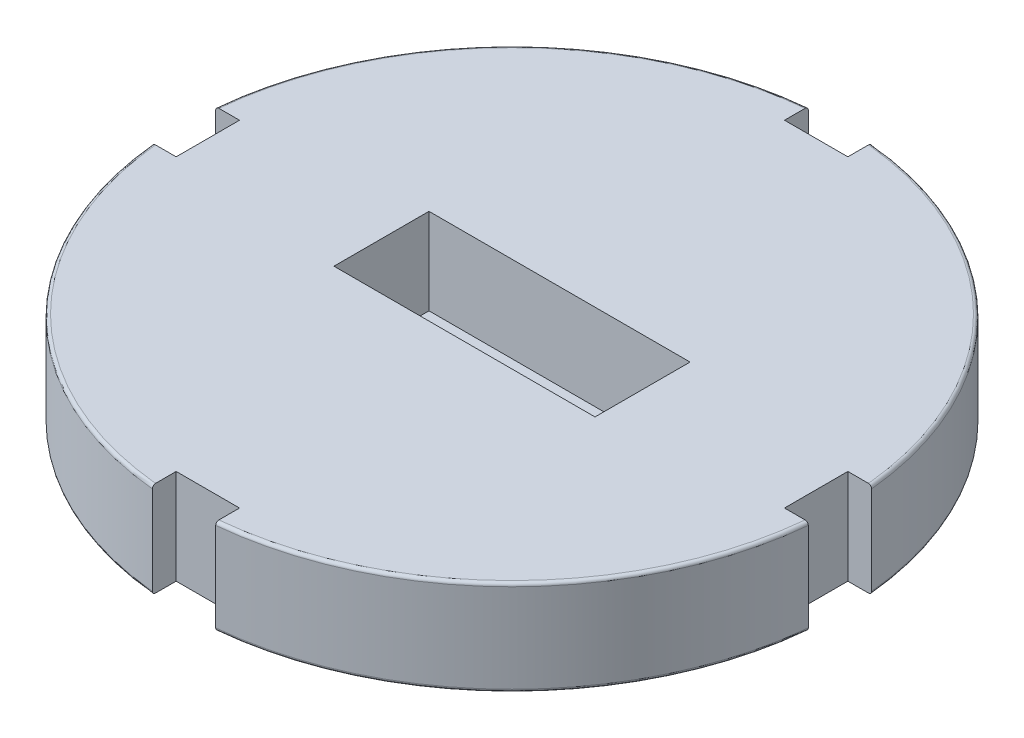
SolidWorks part; units mm, degrees
ref_plane "Front" through (0, 0, 0) normal (0, 0, 1) x (1, 0, 0)
ref_plane "Top" through (0, 0, 0) normal (0, 1, 0) x (1, 0, 0)
ref_plane "Right" through (0, 0, 0) normal (1, 0, 0) x (0, 0, -1)
sketch "Sketch2" plane through (0, 0, 0) normal (0, 1, 0) x (1, 0, 0)
  circle A0 centre (0, 0) radius 66.04
  dimension "D1" = 132.08
extrude "Boss-Extrude1" add sketch "Sketch2" along normal blind 19.05
fillet "Fillet1" radius 0.635 2 edges at (0, 0, 66.04) (0, 19.05, 66.04)
sketch "Sketch3" plane through (0, 19.05, 0) normal (0, 1, 0) x (1, 0, 0)
  circle A0 centre (0, 0) radius 7.62
  dimension "D1" = 15.24
sketch "Sketch4" plane through (0, 0, 0) normal (0, -1, 0) x (1, 0, 0)
  line L0 (-73.4673, 0) -> (74.0346, 0) construction
  line L1 (0, 71.1035) -> (0, -72.2381) construction
  line L2 (-12.7646, 0) -> (-12.7646, -60.96) construction
  line L3 (6.35, -70.0594) -> (-6.35, -70.0594)
  line L4 (-6.35, -70.0594) -> (-6.35, -60.96)
  line L5 (-6.35, -60.96) -> (6.35, -60.96)
  line L6 (6.35, -60.96) -> (6.35, -70.0594)
  line L7 (-60.96, -6.35) -> (-70.0594, -6.35)
  line L8 (-70.0594, -6.35) -> (-70.0594, 6.35)
  line L9 (-70.0594, 6.35) -> (-60.96, 6.35)
  line L10 (-60.96, 6.35) -> (-60.96, -6.35)
  line L11 (-6.35, 60.96) -> (-6.35, 70.0594)
  line L12 (-6.35, 70.0594) -> (6.35, 70.0594)
  line L13 (6.35, 70.0594) -> (6.35, 60.96)
  line L14 (6.35, 60.96) -> (-6.35, 60.96)
  line L15 (60.96, 6.35) -> (70.0594, 6.35)
  line L16 (70.0594, 6.35) -> (70.0594, -6.35)
  line L17 (70.0594, -6.35) -> (60.96, -6.35)
  line L18 (60.96, -6.35) -> (60.96, 6.35)
  point P10 (0, -70.0594)
  point P27 (0, 0)
  dimension "D1" = 60.96
  dimension "D2" = 6.35
  dimension "D3" = 4
extrude "Cut-Extrude2" cut sketch "Sketch4" against normal through all
sketch "Sketch5" plane through (0, 19.05, 0) normal (0, 1, 0) x (1, 0, 0)
  line L0 (-74.4557, 0) -> (79.5515, 0) construction
  line L1 (0, 74.9275) -> (0, -77.5698) construction
  line L3 (26.162, -9.525) -> (26.162, 9.525)
  line L4 (26.162, 9.525) -> (-26.162, 9.525)
  line L5 (-26.162, -9.525) -> (-26.162, 9.525)
  line L6 (26.162, -9.525) -> (-26.162, -9.525)
  point P11 (0, 9.525)
  point P13 (-26.162, 0)
  dimension "D1" = 26.162
extrude "Cut-Extrude3" cut sketch "Sketch5" against normal blind 17.272
